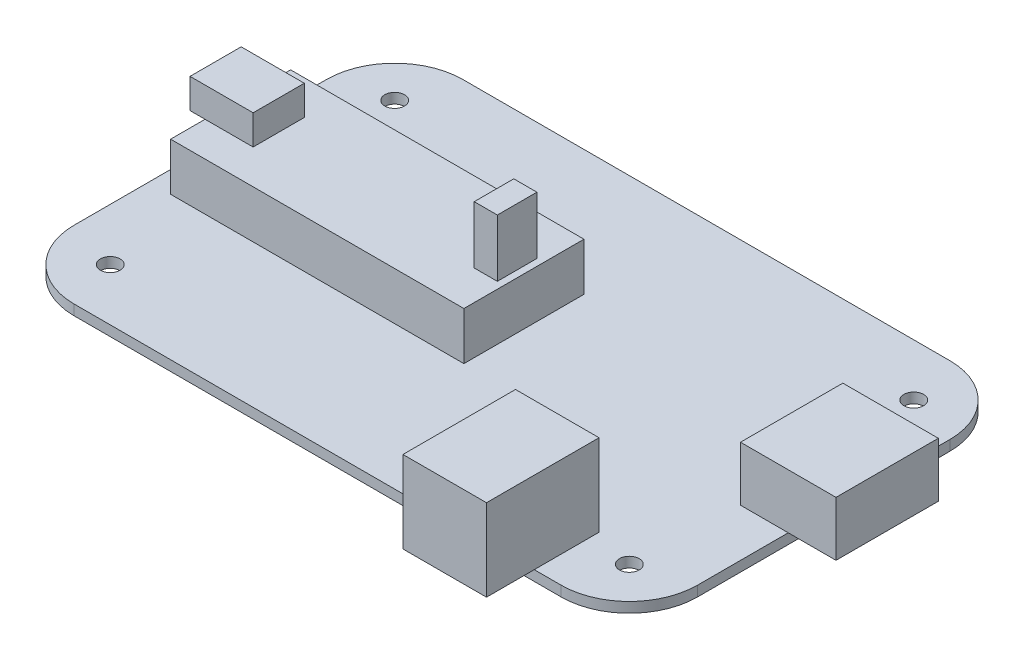
SolidWorks part; units mm, degrees
ref_plane "Front Plane" through (0, 0, 0) normal (0, 0, 1) x (1, 0, 0)
ref_plane "Top Plane" through (0, 0, 0) normal (0, 1, 0) x (1, 0, 0)
ref_plane "Right Plane" through (0, 0, 0) normal (1, 0, 0) x (0, 0, -1)
sketch "Sketch1" plane through (0, 0, 0) normal (0, 1, 0) x (1, 0, 0)
  line L1 (-35.7, 28.5) -> (35.7, 28.5)
  line L2 (-45.7, 18.5) -> (-45.7, -18.5)
  line L3 (-35.7, -28.5) -> (35.7, -28.5)
  line L4 (45.7, 18.5) -> (45.7, -18.5)
  line L5 (-45.7, 28.5) -> (45.7, -28.5) construction
  line L6 (-45.7, -28.5) -> (45.7, 28.5) construction
  arc A0 (35.7, 28.5) -> (45.7, 18.5) centre (35.7, 18.5) cw
  arc A1 (35.7, -28.5) -> (45.7, -18.5) centre (35.7, -18.5) ccw
  arc A2 (-45.7, -18.5) -> (-35.7, -28.5) centre (-35.7, -18.5) ccw
  arc A3 (-35.7, 28.5) -> (-45.7, 18.5) centre (-35.7, 18.5) ccw
  circle A4 centre (-38.05, 20.85) radius 1.445
  circle A5 centre (-38.05, -20.85) radius 1.445
  circle A6 centre (38.05, 20.85) radius 1.445
  circle A7 centre (38.05, -20.85) radius 1.445
  point P0 (0, 0)
  dimension "D3" = 10
  dimension "D4" = 7.65
  dimension "D8" = 2.89
  dimension "D1" = 57
  dimension "D2" = 91.4
  dimension "D5" = 7.65
  dimension "D6" = 7.65
  dimension "D7" = 7.65
extrude "Boss-Extrude1" add sketch "Sketch1" along normal blind 1.5
sketch "Sketch2" plane through (0, 1.5, 0) normal (0, 1, 0) x (1, 0, 0)
  line L0 (-45.7, 18.5) -> (-45.7, -18.5) construction
  line L1 (-42.55, -7.5) -> (0.45, -7.5)
  line L2 (-42.55, -7.5) -> (-42.55, 10.1)
  line L3 (-42.55, 10.1) -> (0.45, 10.1)
  line L4 (0.45, -7.5) -> (0.45, 10.1)
  line L5 (-35.7, -28.5) -> (35.7, -28.5) construction
  dimension "D1" = 17.6
  dimension "D2" = 43
  dimension "D3" = 3.15
  dimension "D4" = 21
extrude "Boss-Extrude2" add sketch "Sketch2" along normal blind 7
sketch "Sketch3" plane through (0, 8.5, 0) normal (0, 1, 0) x (1, 0, 0)
  line L0 (-42.55, 1.3) -> (0.45, 1.3) construction
  line L1 (-42.55, 10.1) -> (-42.55, -7.5) construction
  line L2 (0.45, -7.5) -> (0.45, 10.1) construction
  line L4 (-44.75, -2.45) -> (-35.5, -2.45)
  line L5 (-44.75, -2.45) -> (-44.75, 5.05)
  line L6 (-44.75, 5.05) -> (-35.5, 5.05)
  line L7 (-35.5, -2.45) -> (-35.5, 5.05)
  line L8 (-44.75, -2.45) -> (-35.5, 5.05) construction
  line L9 (-44.75, 5.05) -> (-35.5, -2.45) construction
  point P6 (-40.125, 1.3)
  dimension "D1" = 2.2
  dimension "D2" = 9.25
  dimension "D3" = 7.5
extrude "Boss-Extrude3" add sketch "Sketch3" along normal blind 4.35
sketch "Sketch4" plane through (0, 8.5, 0) normal (0, 1, 0) x (1, 0, 0)
  line L0 (0.45, 1.3) -> (-35.5, 1.3) construction
  line L1 (0.45, -7.5) -> (0.45, 10.1) construction
  line L2 (-35.5, -2.45) -> (-35.5, 5.05) construction
  line L4 (-3.94, -1.6) -> (-0.55, -1.6)
  line L5 (-3.94, -1.6) -> (-3.94, 4.2)
  line L6 (-3.94, 4.2) -> (-0.55, 4.2)
  line L7 (-0.55, -1.6) -> (-0.55, 4.2)
  line L8 (-3.94, -1.6) -> (-0.55, 4.2) construction
  line L9 (-3.94, 4.2) -> (-0.55, -1.6) construction
  point P6 (-2.245, 1.3)
  dimension "D1" = 3.39
  dimension "D2" = 5.8
  dimension "D3" = 1
extrude "Boss-Extrude4" add sketch "Sketch4" along normal blind 8.42
sketch "Sketch5" plane through (0, 1.5, 0) normal (0, 1, 0) x (1, 0, 0)
  line L0 (45.7, -18.5) -> (45.7, 18.5) construction
  line L1 (52.7, 9.8) -> (38.7, 9.8)
  line L2 (52.7, 9.8) -> (52.7, -5.2)
  line L3 (52.7, -5.2) -> (38.7, -5.2)
  line L4 (38.7, 9.8) -> (38.7, -5.2)
  line L5 (52.7, 9.8) -> (38.7, -5.2) construction
  line L6 (52.7, -5.2) -> (38.7, 9.8) construction
  line L7 (-35.7, -28.5) -> (35.7, -28.5) construction
  point P0 (45.7, 2.3)
  dimension "D1" = 14
  dimension "D2" = 15
  dimension "D3" = 7
  dimension "D4" = 23.3
extrude "Boss-Extrude5" add sketch "Sketch5" along normal blind 8
sketch "Sketch6" plane through (0, 1.5, 0) normal (0, 1, 0) x (1, 0, 0)
  line L0 (-35.7, -28.5) -> (35.7, -28.5) construction
  line L1 (31.7621, -19) -> (19.5121, -19)
  line L2 (31.7621, -19) -> (31.7621, -35.5)
  line L3 (31.7621, -35.5) -> (19.5121, -35.5)
  line L4 (19.5121, -19) -> (19.5121, -35.5)
  line L5 (31.7621, -19) -> (19.5121, -35.5) construction
  line L6 (31.7621, -35.5) -> (19.5121, -19) construction
  point P0 (25.6371, -27.25)
  dimension "D1" = 7
  dimension "D2" = 12.25
  dimension "D3" = 16.5
extrude "Boss-Extrude6" add sketch "Sketch6" along normal blind 12
equation "\"D6@Sketch1\"=\"D5@Sketch1\""
